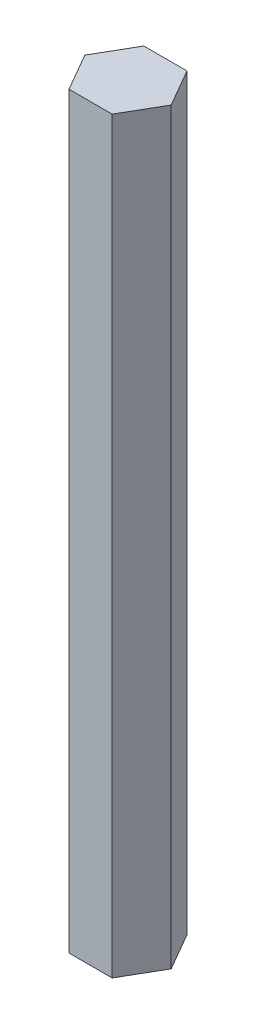
SolidWorks part; units mm, degrees
ref_plane "Front Plane" through (0, 0, 0) normal (0, 0, 1) x (1, 0, 0)
ref_plane "Top Plane" through (0, 0, 0) normal (0, 1, 0) x (1, 0, 0)
ref_plane "Right Plane" through (0, 0, 0) normal (1, 0, 0) x (0, 0, -1)
sketch "Sketch1" plane through (0, 0, 0) normal (0, 1, 0) x (1, 0, 0)
  line L1 (2.8868, 0) -> (1.4434, 2.5)
  line L2 (1.4434, 2.5) -> (-1.4434, 2.5)
  line L3 (-1.4434, 2.5) -> (-2.8868, 0)
  line L4 (-2.8868, 0) -> (-1.4434, -2.5)
  line L5 (-1.4434, -2.5) -> (1.4434, -2.5)
  line L6 (1.4434, -2.5) -> (2.8868, 0)
  circle A0 centre (0, 0) radius 2.5 construction
extrude "Boss-Extrude1" add sketch "Sketch1" along normal blind 50
